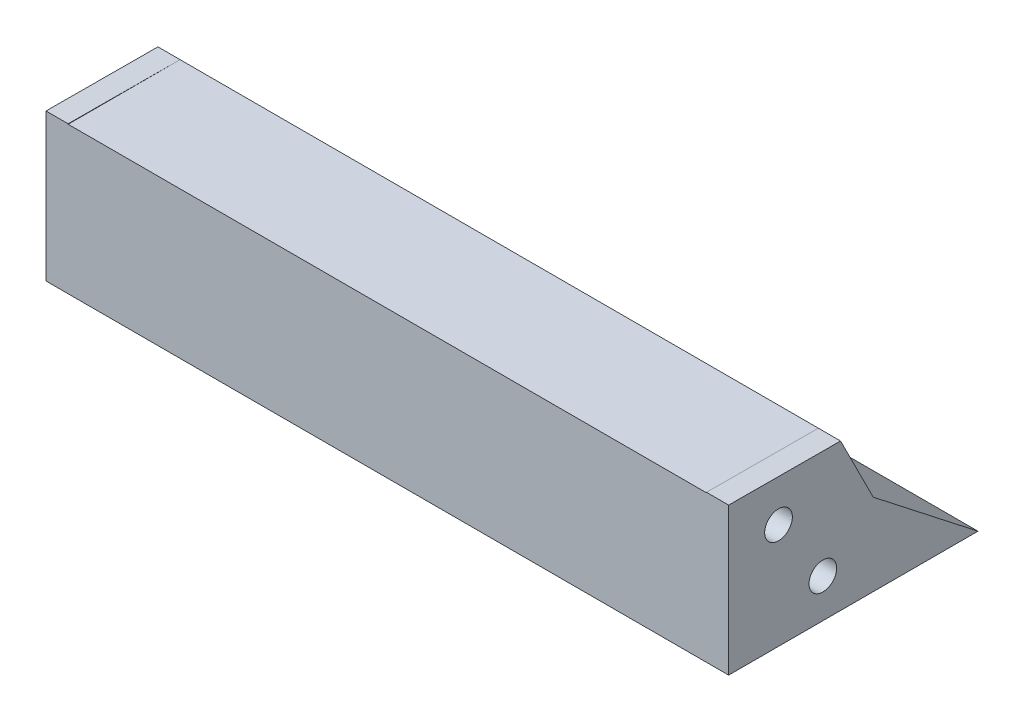
SolidWorks part; units mm, degrees
ref_plane "Front Plane" through (0, 0, 0) normal (0, 0, 1) x (1, 0, 0)
ref_plane "Top Plane" through (0, 0, 0) normal (0, 1, 0) x (1, 0, 0)
ref_plane "Right Plane" through (0, 0, 0) normal (1, 0, 0) x (0, 0, -1)
sketch "Sketch1" plane through (0, 0, 0) normal (1, 0, 0) x (0, 0, -1)
  line L0 (-4.25, 0) -> (-4.25, -4)
  line L1 (-1.45, -21) -> (21.05, -21)
  line L3 (21.05, -21) -> (11.5939, -13.6121)
  line L4 (11.5939, -13.6121) -> (3.7978, 1.9077)
  line L5 (-161.4, -23) -> (38.6, -23) construction
  line L6 (-3.6993, -5.1614) -> (-2.0007, -6.5499)
  line L7 (-1.45, -7.7112) -> (-1.45, -21)
  circle A0 centre (0, 0) radius 2.15
  arc A1 (3.7978, 1.9077) -> (-4.25, 0) centre (0, 0) ccw
  arc A2 (-4.25, -4) -> (-3.6993, -5.1614) centre (-2.75, -4) ccw
  arc A3 (-1.45, -7.7112) -> (-2.0007, -6.5499) centre (-2.95, -7.7112) ccw
  point P16 (-1.45, -7)
  dimension "D1" = 4.3
  dimension "D2" = 8.5
  dimension "D8" = 21
  dimension "D3" = 1.5
  dimension "D4" = 14
  dimension "D10" = 1.5
  dimension "D5" = 38
  dimension "D6" = 12
  dimension "D7" = 2
  dimension "D9" = 2.8
  dimension "D11" = 4
  dimension "D12" = 22.5
extrude "Boss-Extrude1" add sketch "Sketch1" along normal mid plane 62.6
sketch "Sketch2" plane through (0, 0, 4.25) normal (0, 0, 1) x (1, 0, 0)
  line L0 (31.3, 4.25) -> (-31.3, 4.25) construction
  line L1 (-28.8, 4.25) -> (28.8, 4.25)
  line L2 (-28.8, 4.25) -> (-28.8, -7.75)
  line L3 (-28.8, -7.75) -> (28.8, -7.75)
  line L4 (28.8, 4.25) -> (28.8, -7.75)
  line L5 (-31.3, 0) -> (-31.3, -4) construction
  line L6 (31.3, 0) -> (31.3, -4) construction
  dimension "D1" = 2.5
  dimension "D2" = 2.5
  dimension "D3" = 12
extrude "Cut-Extrude1" cut sketch "Sketch2" against normal up to next
sketch "Sketch8" plane through (31.3, 0, 0) normal (1, 0, 0) x (0, 0, -1)
  line L0 (-1.45, -7.7112) -> (8.6492, -7.75)
  line L1 (-3.6993, -5.1614) -> (-2.0007, -6.5499) construction
  line L2 (-4.25, 0) -> (-4.25, -4) construction
  line L3 (11.5939, -13.6121) -> (3.7978, 1.9077) construction
  line L4 (-3.6993, -5.1614) -> (-2.0007, -6.5499)
  line L5 (-4.25, 0) -> (-4.25, -4)
  line L6 (8.6492, -7.75) -> (3.7978, 1.9077)
  arc A0 (-1.45, -7.7112) -> (-2.0007, -6.5499) centre (-2.95, -7.7112) ccw construction
  arc A1 (-4.25, -4) -> (-3.6993, -5.1614) centre (-2.75, -4) ccw construction
  arc A2 (3.7978, 1.9077) -> (-4.25, 0) centre (0, 0) ccw construction
  arc A3 (-1.45, -7.7112) -> (-2.0007, -6.5499) centre (-2.95, -7.7112) ccw
  arc A4 (-4.25, -4) -> (-3.6993, -5.1614) centre (-2.75, -4) ccw
  arc A5 (3.7978, 1.9077) -> (-4.25, 0) centre (0, 0) ccw
extrude "Cut-Extrude3" cut sketch "Sketch8" against normal through all
fillet "Fillet1" [suppressed] radius 2
sketch "Sketch9" plane through (0, -7.75, 0) normal (0, 1, 0) x (1, 0, 0)
  line L0 (31.3, -1.45) -> (31.3, 8.6492) construction
  line L1 (-30.8, -25.05) -> (30.8, -25.05)
  line L2 (-30.8, -25.05) -> (-30.8, 25.05)
  line L3 (-30.8, 25.05) -> (30.8, 25.05)
  line L4 (30.8, -25.05) -> (30.8, 25.05)
  line L5 (-30.8, -25.05) -> (30.8, 25.05) construction
  line L6 (-30.8, 25.05) -> (30.8, -25.05) construction
  line L7 (-31.3, -26.05) -> (31.3, -26.05)
  line L8 (-31.3, -26.05) -> (-31.3, 26.05)
  line L9 (-31.3, 26.05) -> (31.3, 26.05)
  line L10 (31.3, -26.05) -> (31.3, 26.05)
  line L11 (-31.3, -26.05) -> (31.3, 26.05) construction
  line L12 (-31.3, 26.05) -> (31.3, -26.05) construction
  line L13 (31.3, 21.05) -> (-31.3, 21.05) construction
  point P0 (0, 0)
  point P6 (0, 0)
  dimension "D1" = 1
  dimension "D2" = 5
  dimension "D3" = 0.5
extrude "Cut-Extrude4" cut sketch "Sketch9" against normal through all and the other way through all
sketch "Sketch10" plane through (30.8, 0, 0) normal (1, 0, 0) x (0, 0, -1)
  circle A0 centre (3.05, -11.5) radius 1.25
  circle A1 centre (7.05, -17.5) radius 1.25
  dimension "D1" = 2.5
extrude "Cut-Extrude5" cut sketch "Sketch10" against normal blind 12
sketch "Sketch11" plane through (-30.8, 0, 0) normal (-1, 0, 0) x (0, 0, 1)
  circle A1 centre (-7.05, -17.5) radius 1.25
  circle A2 centre (-7.05, -17.5) radius 1.25
  circle A3 centre (-3.05, -11.5) radius 1.25
  circle A4 centre (-3.05, -11.5) radius 1.25
  dimension "D1" = 0
  dimension "D2" = 0
extrude "Cut-Extrude6" cut sketch "Sketch11" against normal blind 12
